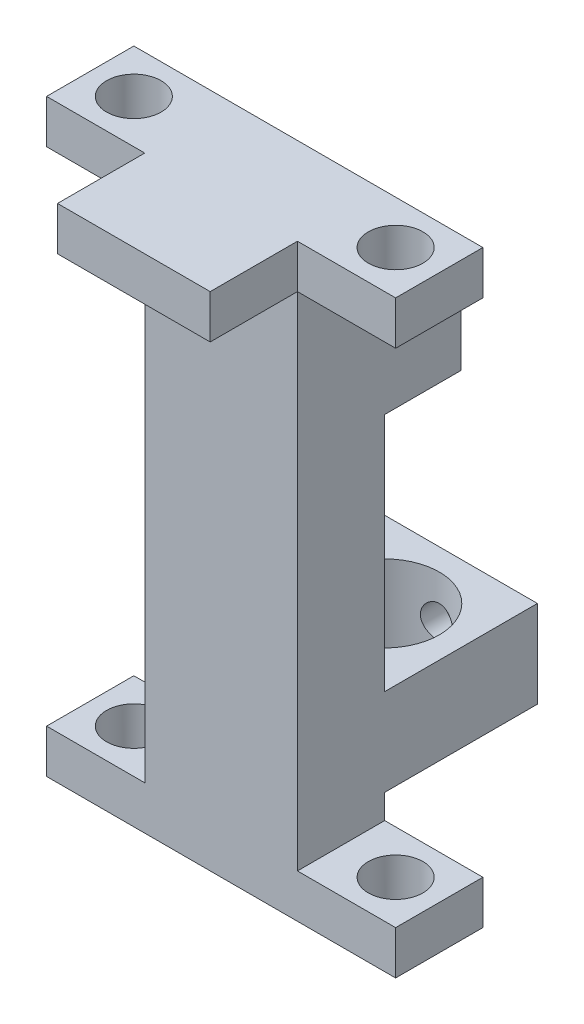
SolidWorks part; units mm, degrees
ref_plane "Plan de face" through (0, 0, 0) normal (0, 0, 1) x (1, 0, 0)
ref_plane "Plan de dessus" through (0, 0, 0) normal (0, 1, 0) x (1, 0, 0)
ref_plane "Plan de droite" through (0, 0, 0) normal (1, 0, 0) x (0, 0, -1)
sketch "Esquisse1" plane through (0, 0, 0) normal (0, 0, 1) x (1, 0, 0)
  line L1 (0, 0) -> (32, 0)
  line L2 (0, 0) -> (0, 54)
  line L3 (0, 54) -> (32, 54)
  line L4 (32, 0) -> (32, 54)
  dimension "D1" = 54
  dimension "D2" = 32
extrude "Boss.-Extru.1" add sketch "Esquisse1" along normal blind 8 contours L2 L3 L4 L1
sketch "Esquisse2" plane through (0, 0, 8) normal (0, 0, 1) x (1, 0, 0)
  line L0 (32, 0) -> (32, 54) construction
  line L1 (0, 54) -> (32, 54)
  line L2 (0, 54) -> (0, 50)
  line L3 (0, 50) -> (32, 50)
  line L4 (32, 54) -> (32, 50)
  dimension "D1" = 4
extrude "Boss.-Extru.2" add sketch "Esquisse2" along normal blind 10 contours L3 L4 L1 L2
sketch "Esquisse3" plane through (32, 0, 0) normal (1, 0, 0) x (0, 0, -1)
  line L0 (-8, 0) -> (-8, 50) construction
  line L5 (0, 0) -> (0, 54) construction
  line L6 (-8, 0) -> (0, 0) construction
  line L7 (-8, 50) -> (0, 50)
  line L8 (-8, 50) -> (-8, 4)
  line L9 (-8, 4) -> (0, 4)
  line L10 (0, 50) -> (0, 4)
  dimension "D1" = 46
  dimension "D2" = 4
extrude "Enlèv. mat.-Extru.1" cut sketch "Esquisse3" against normal blind 9
sketch "Esquisse4" plane through (0, 0, 0) normal (-1, 0, 0) x (0, 0, 1)
  line L0 (0, 0) -> (0, 54) construction
  line L1 (0, 50) -> (8, 50)
  line L2 (0, 50) -> (0, 4)
  line L3 (0, 4) -> (8, 4)
  line L4 (8, 50) -> (8, 4)
  line L5 (8, 0) -> (8, 50) construction
  line L6 (8, 0) -> (0, 0) construction
  dimension "D1" = 46
  dimension "D2" = 4
extrude "Enlèv. mat.-Extru.2" cut sketch "Esquisse4" against normal blind 9
sketch "Esquisse5" plane through (0, 54, 0) normal (0, 1, 0) x (1, 0, 0)
  line L0 (0, 0) -> (32, 0) construction
  line L1 (0, -18) -> (0, 0) construction
  line L2 (32, -18) -> (32, 0) construction
  circle A0 centre (4, -4) radius 2.5
  circle A1 centre (28, -4) radius 2.5
  dimension "D1" = 5
  dimension "D2" = 5
  dimension "D3" = 4
  dimension "D4" = 4
  dimension "D5" = 4
  dimension "D6" = 4
extrude "Enlèv. mat.-Extru.3" cut sketch "Esquisse5" against normal blind 54
sketch "Esquisse6" plane through (0, 0, 0) normal (0, 0, -1) x (-1, 0, 0)
  line L0 (-23, 4) -> (-23, 50) construction
  line L1 (-23, 14.2403) -> (-9, 14.2403)
  line L2 (-23, 14.2403) -> (-23, 6.2403)
  line L3 (-23, 6.2403) -> (-9, 6.2403)
  line L4 (-9, 14.2403) -> (-9, 6.2403)
  line L5 (-9, 50) -> (-9, 4) construction
  dimension "D1" = 8
extrude "Boss.-Extru.3" add sketch "Esquisse6" along normal blind 14
sketch "Esquisse9" plane through (0, 54, 0) normal (0, 1, 0) x (1, 0, 0)
  line L0 (0, 0) -> (32, 0) construction
  line L1 (23, -18) -> (32, -18)
  line L2 (23, -18) -> (23, -8)
  line L3 (23, -8) -> (32, -8)
  line L4 (32, -18) -> (32, -8)
  line L5 (0, -18) -> (9, -18)
  line L6 (0, -18) -> (0, -8)
  line L7 (0, -8) -> (9, -8)
  line L8 (9, -18) -> (9, -8)
  line L9 (0, -18) -> (32, -18) construction
  line L10 (32, -18) -> (32, 0) construction
  line L11 (0, -18) -> (0, 0) construction
  point P14 (4.5, -8)
  dimension "D1" = 8
  dimension "D2" = 0
  dimension "D3" = 0
  dimension "D4" = 8
  dimension "D5" = 0
  dimension "D6" = 0
  dimension "D7" = 9
  dimension "D8" = 9
extrude "Enlèv. mat.-Extru.6" cut sketch "Esquisse9" against normal blind 4
sketch "Esquisse10" plane through (0, 0, 0) normal (0, 0, -1) x (-1, 0, 0)
  line L0 (-9, 50) -> (-9, 14.2403) construction
  line L1 (-23, 42.2403) -> (-9, 42.2403)
  line L2 (-23, 42.2403) -> (-23, 36.2403)
  line L3 (-23, 36.2403) -> (-9, 36.2403)
  line L4 (-9, 42.2403) -> (-9, 36.2403)
  line L5 (-23, 14.2403) -> (-23, 50) construction
  line L7 (-9, 14.2403) -> (-23, 14.2403) construction
  dimension "D1" = 0
  dimension "D2" = 0
  dimension "D3" = 6
  dimension "D4" = 22
extrude "Boss.-Extru.4" add sketch "Esquisse10" along normal blind 7
sketch "Esquisse7" plane through (0, 14.2403, 0) normal (0, 1, 0) x (1, 0, 0)
  line L0 (9, 14) -> (23, 14) construction
  line L1 (23, 14) -> (23, 0) construction
  circle A0 centre (16, 7) radius 5
  dimension "D1" = 10
  dimension "D2" = 7
  dimension "D3" = 7
extrude "Enlèv. mat.-Extru.4" cut sketch "Esquisse7" against normal through all
sketch "Esquisse8" plane through (0, 0, -14) normal (0, 0, -1) x (-1, 0, 0)
  line L0 (-23, 14.2403) -> (-23, 6.2403) construction
  line L1 (-23, 6.2403) -> (-9, 6.2403) construction
  circle A0 centre (-16, 10.2403) radius 1.5
  dimension "D1" = 3
  dimension "D2" = 7
  dimension "D3" = 4
extrude "Enlèv. mat.-Extru.5" cut sketch "Esquisse8" against normal blind 7
sketch "Esquisse11" plane through (0, 42.2403, 0) normal (0, 1, 0) x (1, 0, 0)
  line L0 (21, 7) -> (16, 2)
  line L1 (16, 2) -> (11, 7)
  line L2 (11, 7) -> (21, 7)
  circle A0 centre (16, 7) radius 5 construction
  dimension "D1" = 45
extrude "Enlèv. mat.-Extru.7" cut sketch "Esquisse11" against normal blind 6
sketch "Esquisse12" plane through (0, 54, 0) normal (0, 1, 0) x (1, 0, 0)
  line L0 (9, -18) -> (23, -18) construction
  line L1 (9, -18) -> (23, -18)
  line L2 (9, -18) -> (9, -16)
  line L3 (9, -16) -> (23, -16)
  line L4 (23, -18) -> (23, -16)
  line L5 (23, -8) -> (23, -18) construction
  line L6 (9, -18) -> (9, -8) construction
  dimension "D1" = 0
  dimension "D2" = 0
  dimension "D3" = 0
  dimension "D4" = 2
extrude "Enlèv. mat.-Extru.8" cut sketch "Esquisse12" against normal through all
